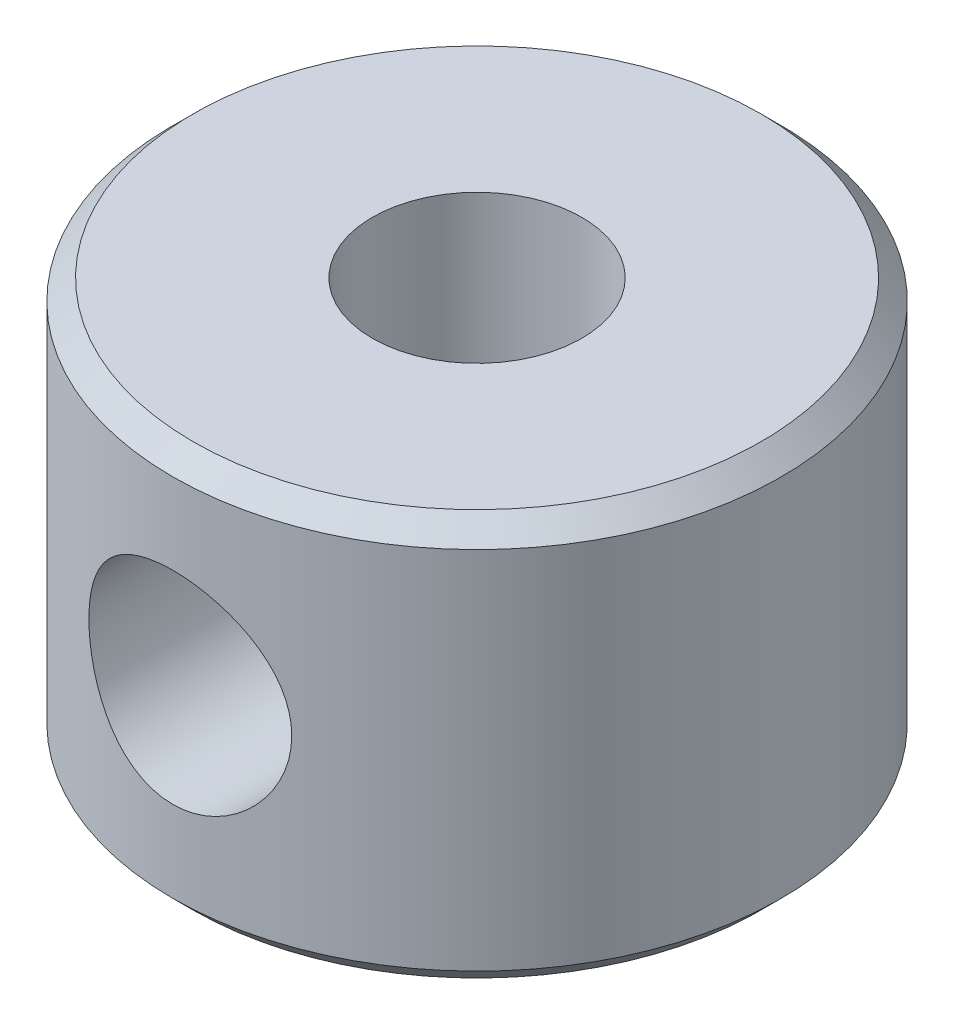
SolidWorks part; units mm, degrees
ref_plane "Alzado" through (0, 0, 0) normal (0, 0, 1) x (1, 0, 0)
ref_plane "Planta" through (0, 0, 0) normal (0, 1, 0) x (1, 0, 0)
ref_plane "Vista lateral" through (0, 0, 0) normal (1, 0, 0) x (0, 0, -1)
sketch "Croquis1" plane through (0, 0, 0) normal (0, 1, 0) x (1, 0, 0)
  circle A0 centre (0, 0) radius 4.5
  dimension "D1" = 9
extrude "Saliente-Extruir1" add sketch "Croquis1" along normal blind 6
chamfer "Chaflán1" distance 0.3 angle 45 1 edges at (0, 6, 4.5)
chamfer "Chaflán2" distance 0.3 angle 45 1 edges at (0, 0, 4.5)
sketch "Croquis2" plane through (0, 6, 0) normal (0, 1, 0) x (1, 0, 0)
  circle A0 centre (0, 0) radius 1.55
extrude "Cortar-Extruir2" cut sketch "Croquis2" against normal blind 6
hole_wizard "Perforador para roscar Helicoil de M2.21" positions "Croquis3D7" profile "Croquis8" hole size "M2.2x0.45" standard "Ansi Metric"
sketch3d "Croquis3D7"
  point P0 (0.0013, 3.0039, 4.5)
sketch "Croquis8" plane through (0.0013, 3.0039, 4.5) normal (0, 1, 0) x (1, 0, -0.0003)
  line L0 (0, 0) -> (0, 2.95)
  line L1 (0, 2.95) -> (1.5, 2.95)
  line L2 (1.5, 2.95) -> (1.5, 0)
  line L5 (1.5, 0) -> (0, 0)
  line L11 (0, -6.35) -> (0, 107.95) construction
  dimension "Diámetro de taladro hasta el siguiente" = 3
  dimension "Profundidad de taladro hasta el siguiente" = 2.95
